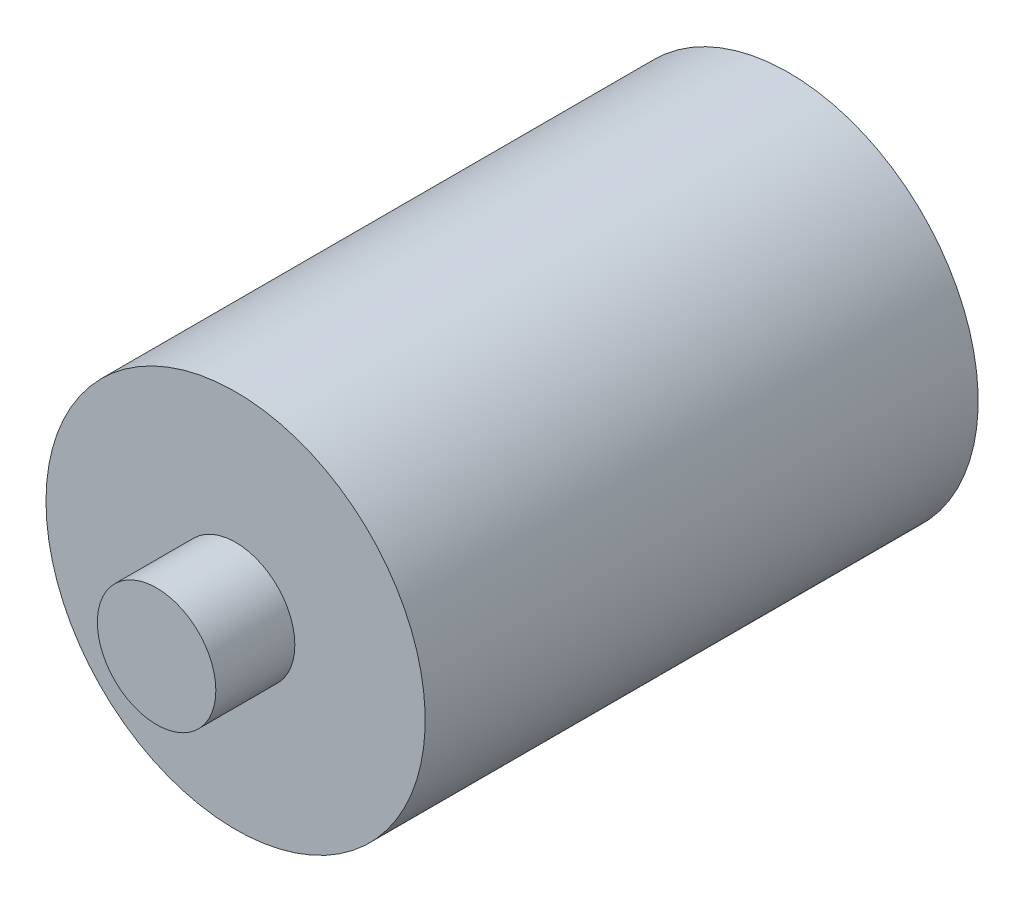
SolidWorks part; units mm, degrees
ref_plane "前视基准面" through (0, 0, 0) normal (0, 0, 1) x (1, 0, 0)
ref_plane "上视基准面" through (0, 0, 0) normal (0, 1, 0) x (1, 0, 0)
ref_plane "右视基准面" through (0, 0, 0) normal (1, 0, 0) x (0, 0, -1)
sketch "草图1" plane through (0, 0, 0) normal (0, 0, 1) x (1, 0, 0)
  circle A0 centre (0, 0) radius 15
  dimension "D1" = 30
extrude "凸台-拉伸1" add sketch "草图1" along normal blind 20
sketch "草图2" plane through (0, 0, 0) normal (0, 0, -1) x (-1, 0, 0)
  circle A0 centre (0, 0) radius 48
  dimension "D1" = 96
extrude "凸台-拉伸2" add sketch "草图2" along normal blind 140
sketch "草图3" plane through (0, 0, -140) normal (0, 0, -1) x (-1, 0, 0)
  circle A0 centre (0, 0) radius 15
  dimension "D1" = 30
extrude "凸台-拉伸3" add sketch "草图3" along normal blind 20
